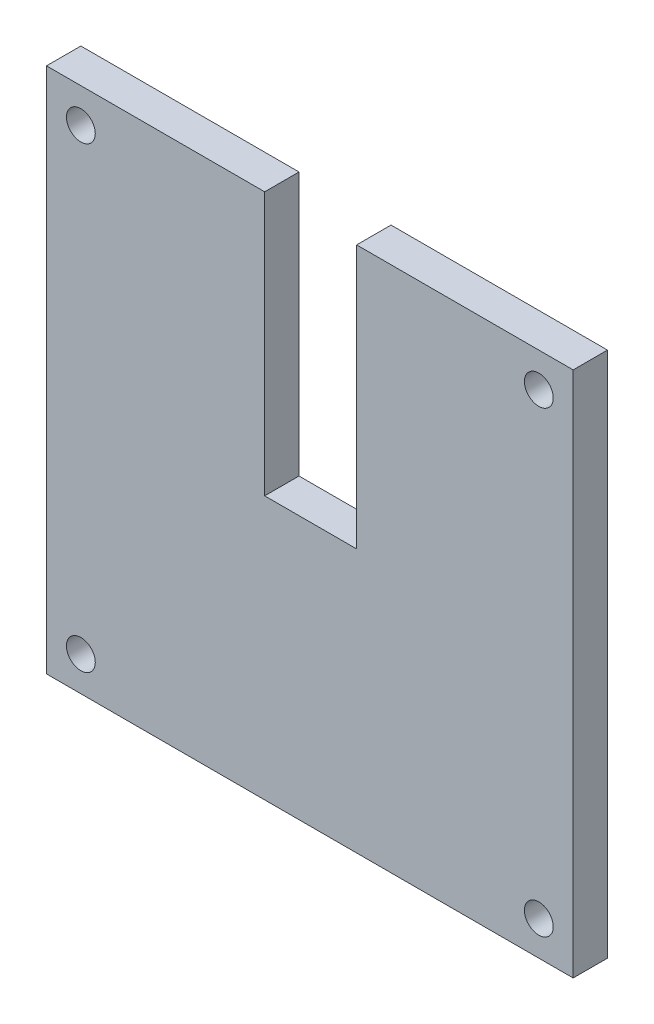
SolidWorks part; units mm, degrees
ref_plane "Front Plane" through (0, 0, 0) normal (0, 0, 1) x (1, 0, 0)
ref_plane "Top Plane" through (0, 0, 0) normal (0, 1, 0) x (1, 0, 0)
ref_plane "Right Plane" through (0, 0, 0) normal (1, 0, 0) x (0, 0, -1)
sketch "Sketch1" plane through (0, 0, 0) normal (0, 0, 1) x (1, 0, 0)
  line L0 (-29.21, -29.21) -> (-4.9563, -29.21) construction
  line L1 (29.21, 29.21) -> (-29.21, 29.21)
  line L2 (29.21, 29.21) -> (29.21, -29.21)
  line L3 (29.21, -29.21) -> (-29.21, -29.21)
  line L4 (-29.21, 29.21) -> (-29.21, -29.21)
  line L5 (29.21, 29.21) -> (-29.21, -29.21) construction
  line L6 (29.21, -29.21) -> (-29.21, 29.21) construction
  line L7 (29.21, -29.21) -> (5.108, -29.21) construction
  point P0 (0, 0)
  dimension "D1" = 58.42
  dimension "D2" = 58.42
extrude "Boss-Extrude1" add sketch "Sketch1" along normal blind 3.81
sketch "Sketch2" plane through (0, 0, 3.81) normal (0, 0, 1) x (1, 0, 0)
  line L0 (-29.21, 29.21) -> (-25.4, 25.4) construction
  line L1 (29.21, 29.21) -> (25.4, 25.4) construction
  line L2 (29.21, -29.21) -> (29.21, 29.21) construction
  line L3 (29.21, 29.21) -> (-29.21, 29.21) construction
  line L4 (-29.21, -29.21) -> (-25.4, -25.4) construction
  line L5 (29.21, -29.21) -> (25.4, -25.4) construction
  circle A0 centre (-25.4, 25.4) radius 1.6
  circle A1 centre (25.4, 25.4) radius 1.6
  circle A2 centre (-25.4, -25.4) radius 1.6
  circle A3 centre (25.4, -25.4) radius 1.6
  dimension "D2" = 3.2
  dimension "D6" = 3.2
  dimension "D7" = 3.2
  dimension "D8" = 3.2
  dimension "D1" = 5.3882
  dimension "D3" = 5.3882
  dimension "D4" = 5.3882
  dimension "D5" = 5.3882
extrude "Cut-Extrude1" cut sketch "Sketch2" against normal blind 3.81
sketch "Sketch5" plane through (0, 0, 3.81) normal (0, 0, 1) x (1, 0, 0)
  line L0 (-29.21, 29.21) -> (-5.0092, 29.21) construction
  line L1 (29.21, 29.21) -> (-29.21, 29.21) construction
  line L2 (29.21, 29.21) -> (5.193, 29.21) construction
  line L4 (-5.0092, 29.21) -> (5.193, 29.21)
  line L5 (-5.0092, 29.21) -> (-5.0092, 0)
  line L6 (-5.0092, 0) -> (5.193, 0)
  line L7 (5.193, 29.21) -> (5.193, 0)
  dimension "D1" = 29.21
extrude "Cut-Extrude3" cut sketch "Sketch5" against normal blind 3.81
